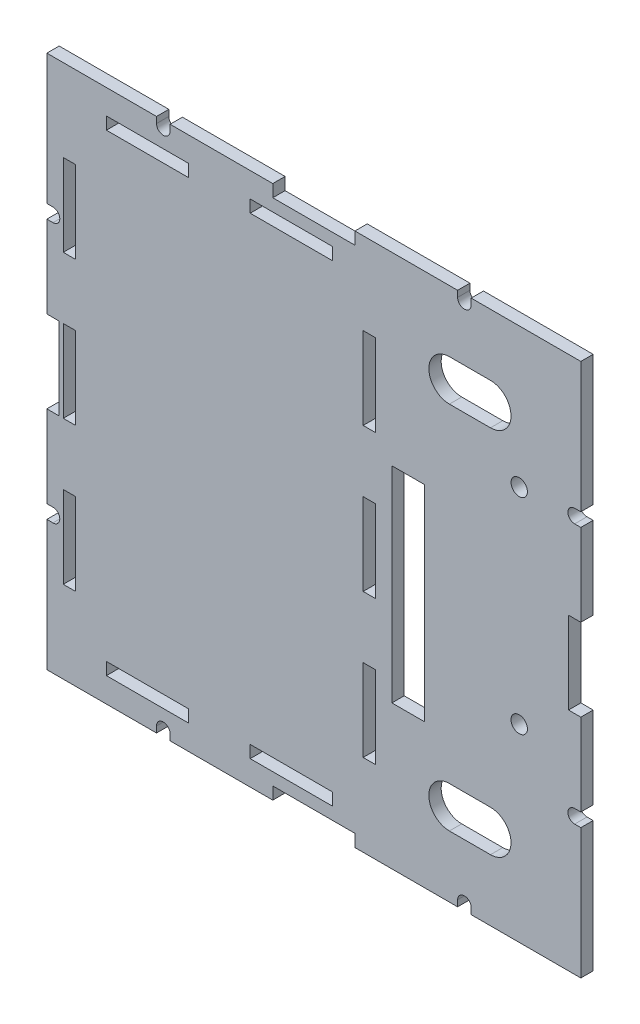
SolidWorks part; units mm, degrees
ref_plane "Front Plane" through (0, 0, 0) normal (0, 0, 1) x (1, 0, 0)
ref_plane "Top Plane" through (0, 0, 0) normal (0, 1, 0) x (1, 0, 0)
ref_plane "Right Plane" through (0, 0, 0) normal (1, 0, 0) x (0, 0, -1)
sketch "Sketch1" plane through (0, 0, 0) normal (0, 0, 1) x (1, 0, 0)
  line L0 (55, 0) -> (-55, 0) construction
  line L1 (65, -65) -> (-65, -65)
  line L2 (65, -65) -> (65, 65)
  line L3 (65, 65) -> (-65, 65)
  line L4 (-65, -65) -> (-65, 65)
  line L5 (65, -65) -> (-65, 65) construction
  line L6 (65, 65) -> (-65, -65) construction
  line L7 (10, 62) -> (-10, 62)
  line L8 (10, 62) -> (10, 65)
  line L9 (10, 65) -> (-10, 65)
  line L10 (-10, 62) -> (-10, 65)
  line L11 (10, 62) -> (-10, 65) construction
  line L12 (10, 65) -> (-10, 62) construction
  line L13 (-62, -10) -> (-65, -10)
  line L14 (-62, -10) -> (-62, 10)
  line L15 (-62, 10) -> (-65, 10)
  line L16 (-65, -10) -> (-65, 10)
  line L17 (-62, -10) -> (-65, 10) construction
  line L18 (-62, 10) -> (-65, -10) construction
  line L19 (10, -65) -> (-10, -65)
  line L20 (-10, -62) -> (-10, -65)
  line L21 (10, -62) -> (-10, -62)
  line L22 (10, -62) -> (10, -65)
  line L23 (0, -55) -> (0, 55) construction
  line L24 (62, 10) -> (65, 10)
  line L25 (65, -10) -> (65, 10)
  line L26 (62, -10) -> (65, -10)
  line L27 (62, -10) -> (62, 10)
  line L28 (-36.65, 63.5) -> (-36.65, 66.5) construction
  line L29 (-38.3, 63.5) -> (-38.3, 66.5)
  line L30 (-35, 63.5) -> (-35, 66.5)
  line L31 (-63.5, 31.65) -> (-66.5, 31.65) construction
  line L32 (-63.5, 30) -> (-66.5, 30)
  line L33 (-63.5, 33.3) -> (-66.5, 33.3)
  line L34 (36.65, 63.5) -> (36.65, 66.5) construction
  line L35 (38.3, 63.5) -> (38.3, 66.5)
  line L36 (35, 63.5) -> (35, 66.5)
  line L37 (63.5, 31.65) -> (66.5, 31.65) construction
  line L38 (63.5, 30) -> (66.5, 30)
  line L39 (63.5, 33.3) -> (66.5, 33.3)
  line L40 (63.5, -31.65) -> (66.5, -31.65) construction
  line L41 (63.5, -30) -> (66.5, -30)
  line L42 (63.5, -33.3) -> (66.5, -33.3)
  line L43 (36.65, -63.5) -> (36.65, -66.5) construction
  line L44 (38.3, -63.5) -> (38.3, -66.5)
  line L45 (35, -63.5) -> (35, -66.5)
  line L46 (-36.65, -63.5) -> (-36.65, -66.5) construction
  line L47 (-38.3, -63.5) -> (-38.3, -66.5)
  line L48 (-35, -63.5) -> (-35, -66.5)
  line L49 (-63.5, -31.65) -> (-66.5, -31.65) construction
  line L50 (-63.5, -30) -> (-66.5, -30)
  line L51 (-63.5, -33.3) -> (-66.5, -33.3)
  line L52 (-58, -45) -> (-61, -45)
  line L53 (-58, -10) -> (-61, -10)
  line L54 (-58, -10) -> (-58, 10)
  line L55 (-58, 10) -> (-61, 10)
  line L56 (-61, -10) -> (-61, 10)
  line L57 (-58, -10) -> (-61, 10) construction
  line L58 (-58, 10) -> (-61, -10) construction
  line L59 (-58, 25) -> (-61, 25)
  line L60 (-58, 25) -> (-58, 45)
  line L61 (-58, 45) -> (-61, 45)
  line L62 (-61, 25) -> (-61, 45)
  line L63 (-58, 25) -> (-61, 45) construction
  line L64 (-58, 45) -> (-61, 25) construction
  line L65 (-61, -25) -> (-61, -45)
  line L66 (-58, -25) -> (-61, -25)
  line L67 (-58, -25) -> (-58, -45)
  line L68 (-15.5, -59) -> (4.5, -59)
  line L69 (-30.5, 56) -> (-50.5, 56)
  line L70 (-30.5, 56) -> (-30.5, 59)
  line L71 (-30.5, 59) -> (-50.5, 59)
  line L72 (-50.5, 56) -> (-50.5, 59)
  line L73 (-30.5, 56) -> (-50.5, 59) construction
  line L74 (-30.5, 59) -> (-50.5, 56) construction
  line L75 (-15.5, 56) -> (4.5, 56)
  line L76 (-15.5, 56) -> (-15.5, 59)
  line L77 (-15.5, 59) -> (4.5, 59)
  line L78 (4.5, 56) -> (4.5, 59)
  line L79 (-15.5, 56) -> (4.5, 59) construction
  line L80 (-15.5, 59) -> (4.5, 56) construction
  line L81 (4.5, -56) -> (4.5, -59)
  line L82 (-15.5, -56) -> (4.5, -56)
  line L83 (-15.5, -56) -> (-15.5, -59)
  line L84 (-30.5, -59) -> (-50.5, -59)
  line L85 (-50.5, -56) -> (-50.5, -59)
  line L86 (-30.5, -56) -> (-50.5, -56)
  line L87 (-30.5, -56) -> (-30.5, -59)
  line L88 (43, -45) -> (33, -45) construction
  line L89 (12, 45) -> (15, 45)
  line L90 (12, 45) -> (12, 25)
  line L91 (12, 25) -> (15, 25)
  line L92 (15, 45) -> (15, 25)
  line L93 (12, 45) -> (15, 25) construction
  line L94 (12, 25) -> (15, 45) construction
  line L95 (15, -10) -> (12, -10)
  line L96 (15, -10) -> (15, 10)
  line L97 (15, 10) -> (12, 10)
  line L98 (12, -10) -> (12, 10)
  line L99 (15, -10) -> (12, 10) construction
  line L100 (15, 10) -> (12, -10) construction
  line L101 (12, -45) -> (15, -45)
  line L102 (12, -45) -> (12, -25)
  line L103 (12, -25) -> (15, -25)
  line L104 (15, -45) -> (15, -25)
  line L105 (12, -45) -> (15, -25) construction
  line L106 (12, -25) -> (15, -45) construction
  line L107 (27, -30) -> (19, -30)
  line L108 (27, -30) -> (27, 20)
  line L109 (27, 20) -> (19, 20)
  line L110 (19, -30) -> (19, 20)
  line L111 (27, -30) -> (19, 20) construction
  line L112 (27, 20) -> (19, -30) construction
  line L117 (43, 45) -> (33, 45) construction
  line L118 (43, 40) -> (33, 40)
  line L119 (43, 50) -> (33, 50)
  line L120 (43, -40) -> (33, -40)
  line L121 (43, -50) -> (33, -50)
  arc A0 (-38.3, 63.5) -> (-35, 63.5) centre (-36.65, 63.5) ccw
  arc A1 (-35, 66.5) -> (-38.3, 66.5) centre (-36.65, 66.5) ccw
  arc A2 (-63.5, 30) -> (-63.5, 33.3) centre (-63.5, 31.65) ccw
  arc A3 (-66.5, 33.3) -> (-66.5, 30) centre (-66.5, 31.65) ccw
  arc A4 (38.3, 63.5) -> (35, 63.5) centre (36.65, 63.5) cw
  arc A5 (35, 66.5) -> (38.3, 66.5) centre (36.65, 66.5) cw
  arc A6 (63.5, 30) -> (63.5, 33.3) centre (63.5, 31.65) cw
  arc A7 (66.5, 33.3) -> (66.5, 30) centre (66.5, 31.65) cw
  arc A8 (63.5, -30) -> (63.5, -33.3) centre (63.5, -31.65) ccw
  arc A9 (66.5, -33.3) -> (66.5, -30) centre (66.5, -31.65) ccw
  arc A10 (38.3, -63.5) -> (35, -63.5) centre (36.65, -63.5) ccw
  arc A11 (35, -66.5) -> (38.3, -66.5) centre (36.65, -66.5) ccw
  arc A12 (-38.3, -63.5) -> (-35, -63.5) centre (-36.65, -63.5) cw
  arc A13 (-35, -66.5) -> (-38.3, -66.5) centre (-36.65, -66.5) cw
  arc A14 (-63.5, -30) -> (-63.5, -33.3) centre (-63.5, -31.65) cw
  arc A15 (-66.5, -33.3) -> (-66.5, -30) centre (-66.5, -31.65) cw
  arc A20 (43, 40) -> (43, 50) centre (43, 45) ccw
  arc A21 (33, 50) -> (33, 40) centre (33, 45) ccw
  circle A22 centre (50, 31) radius 2
  circle A23 centre (50, -19) radius 2
  arc A24 (43, -40) -> (43, -50) centre (43, -45) cw
  arc A25 (33, -50) -> (33, -40) centre (33, -45) cw
  point P0 (0, 0)
  point P6 (0, 63.5)
  point P11 (-63.5, 0)
  point P16 (-36.65, 65)
  point P35 (-65, 31.65)
  point P42 (-59.5, 35)
  point P45 (36.65, 65)
  point P52 (65, 31.65)
  point P59 (65, -31.65)
  point P66 (36.65, -65)
  point P73 (-36.65, -65)
  point P80 (-65, -31.65)
  point P85 (-59.5, 0)
  point P94 (-5.5, 57.5)
  point P100 (-40.5, 57.5)
  point P108 (13.5, -35)
  point P117 (13.5, 35)
  point P123 (13.5, 0)
  point P132 (23, -5)
  point P138 (38, -45)
  point P143 (38, 45)
  dimension "D7" = 1.65
  dimension "D10" = 1.65
  dimension "D29" = 10
  dimension "D31" = 5
  dimension "D35" = 4
  dimension "D1" = 130
  dimension "D2" = 130
  dimension "D3" = 20
  dimension "D4" = 3
  dimension "D5" = 20
  dimension "D6" = 3
  dimension "D8" = 3
  dimension "D9" = 25
  dimension "D11" = 3
  dimension "D12" = 20
  dimension "D13" = 20
  dimension "D14" = 3
  dimension "D15" = 15
  dimension "D16" = 4
  dimension "D17" = 20
  dimension "D18" = 3
  dimension "D19" = 6
  dimension "D20" = 15
  dimension "D21" = 10.5
  dimension "D22" = 10.5
  dimension "D23" = 3
  dimension "D24" = 20
  dimension "D25" = 15
  dimension "D26" = 15
  dimension "D27" = 50
  dimension "D28" = 8
  dimension "5" = 35
  dimension "D30" = 38
  dimension "D32" = 15
  dimension "D33" = 27
  dimension "D36" = 31
  dimension "D37" = 50
  dimension "D38" = 50
extrude "Boss-Extrude1" add sketch "Sketch1" along normal blind 3 contours L26 L27 L24 L2 L3 L8 L7 L10 L4 L15 L14 L13 L1 L20 L21 L22
